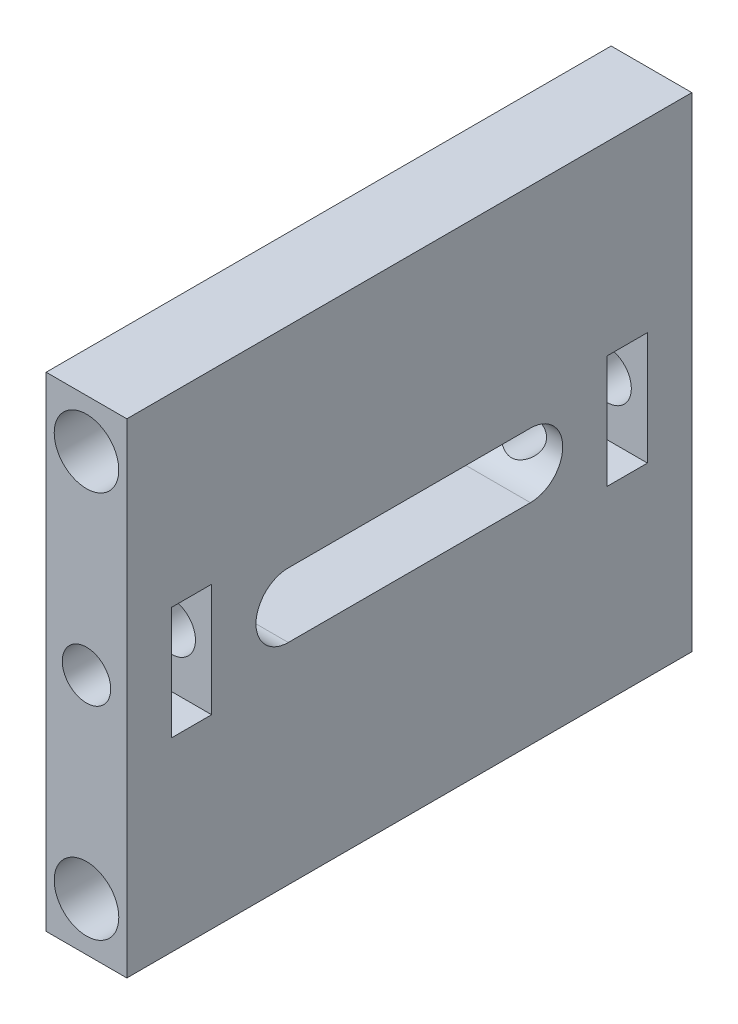
SolidWorks part; units mm, degrees
ref_plane "Plan de face" through (0, 0, 0) normal (0, 0, 1) x (1, 0, 0)
ref_plane "Plan de dessus" through (0, 0, 0) normal (0, 1, 0) x (1, 0, 0)
ref_plane "Plan de droite" through (0, 0, 0) normal (1, 0, 0) x (0, 0, -1)
sketch "Esquisse1" plane through (0, 0, 0) normal (0, 0, 1) x (1, 0, 0)
  line L1 (-2.5, -15) -> (2.5, -15)
  line L2 (-2.5, -15) -> (-2.5, 15)
  line L3 (-2.5, 15) -> (2.5, 15)
  line L4 (2.5, -15) -> (2.5, 15)
  line L5 (-2.5, -15) -> (2.5, 15) construction
  line L6 (-2.5, 15) -> (2.5, -15) construction
  point P0 (0, 0)
  dimension "D1" = 5
  dimension "D2" = 30
extrude "Boss.-Extru.1" add sketch "Esquisse1" along normal blind 35
sketch "Esquisse2" plane through (2.5, 0, 0) normal (1, 0, 0) x (0, 0, -1)
  line L0 (-10, 0) -> (-25, 0) construction
  line L1 (-10, -2) -> (-25, -2)
  line L2 (-10, 2) -> (-25, 2)
  line L4 (-35, 15) -> (0, 15) construction
  line L5 (-35, 15) -> (0, -15) construction
  arc A0 (-10, -2) -> (-10, 2) centre (-10, 0) ccw
  arc A1 (-25, 2) -> (-25, -2) centre (-25, 0) ccw
  point P3 (-17.5, 0)
  dimension "D1" = 2
  dimension "D2" = 15
  dimension "D4" = 15
extrude "Enlèv. mat.-Extru.1" cut sketch "Esquisse2" against normal through all
sketch "Esquisse3" plane through (0, 0, 35) normal (0, 0, 1) x (1, 0, 0)
  line L0 (0, -15) -> (0, 15) construction
  line L1 (-2.5, -15) -> (2.5, -15) construction
  line L2 (2.5, 15) -> (-2.5, 15) construction
  line L3 (-2.5, 0) -> (2.5, 0) construction
  line L4 (-2.5, 15) -> (-2.5, -15) construction
  line L5 (2.5, -15) -> (2.5, 15) construction
  circle A0 centre (0, 0) radius 1.5
  circle A1 centre (0, -12) radius 2
  circle A2 centre (0, 12) radius 2
  dimension "D1" = 3
  dimension "D2" = 4
  dimension "D3" = 3
extrude "Enlèv. mat.-Extru.2" cut sketch "Esquisse3" against normal blind 40
sketch "Esquisse4" plane through (2.5, 0, 0) normal (1, 0, 0) x (0, 0, -1)
  line L0 (-35, 0) -> (0, 0) construction
  line L1 (-35, -15) -> (-35, 15) construction
  line L2 (-35, 15) -> (-35, -15) construction
  line L3 (-29.75, -3.5) -> (-32.25, -3.5)
  line L4 (-29.75, -3.5) -> (-29.75, 3.5)
  line L5 (-29.75, 3.5) -> (-32.25, 3.5)
  line L6 (-32.25, -3.5) -> (-32.25, 3.5)
  line L7 (-29.75, -3.5) -> (-32.25, 3.5) construction
  line L8 (-29.75, 3.5) -> (-32.25, -3.5) construction
  point P5 (-31, 0)
  dimension "D1" = 7
  dimension "D2" = 2.5
  dimension "D3" = 4
extrude "Enlèv. mat.-Extru.3" cut sketch "Esquisse4" against normal blind 10
ref_plane "Plan1" through (0, 0, 17.5) normal (0, 0, 1) x (1, 0, 0)
mirror "Symétrie1" about plane through (0, 0, 17.5) normal (0, 0, 1) of "Enlèv. mat.-Extru.3"
